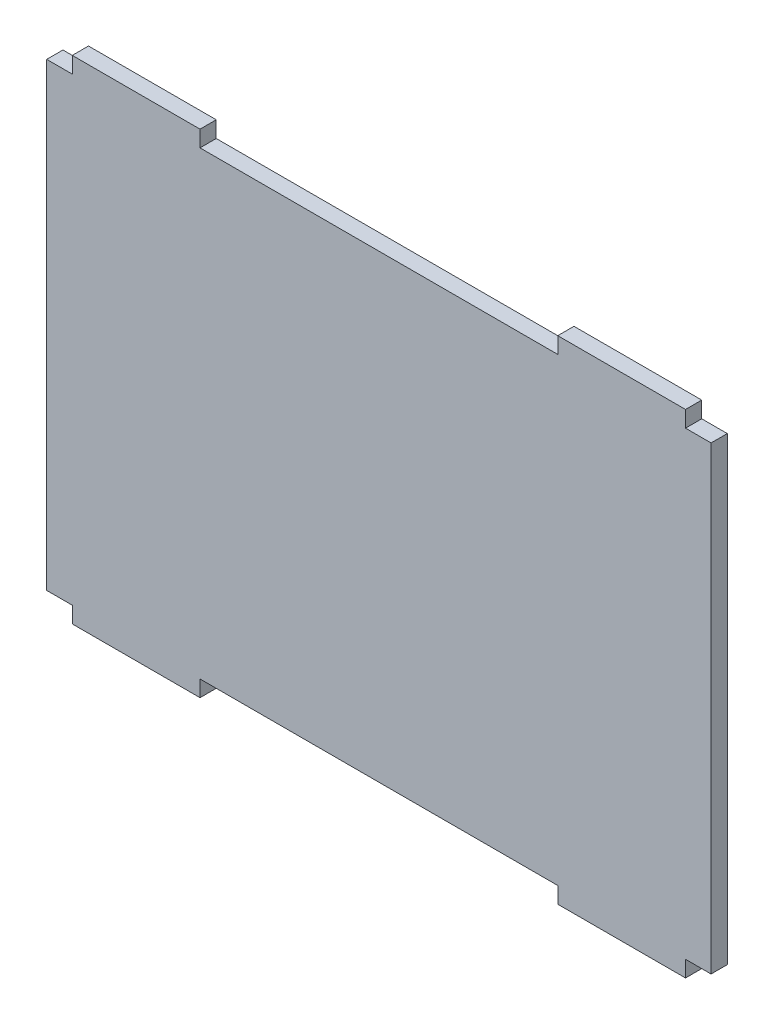
SolidWorks part; units mm, degrees
ref_plane "Front Plane" through (0, 0, 0) normal (0, 0, 1) x (1, 0, 0)
ref_plane "Top Plane" through (0, 0, 0) normal (0, 1, 0) x (1, 0, 0)
ref_plane "Right Plane" through (0, 0, 0) normal (1, 0, 0) x (0, 0, -1)
sketch "Sketch1" plane through (0, 0, 0) normal (0, 0, 1) x (1, 0, 0)
  line L0 (5, 0) -> (5, -3.175)
  line L1 (0, 0) -> (5, 0)
  line L2 (0, 0) -> (0, 90)
  line L3 (0, 90) -> (5, 90)
  line L4 (130, 0) -> (130, 90)
  line L5 (5, -3.175) -> (30, -3.175)
  line L6 (30, -3.175) -> (30, 0)
  line L7 (125, 0) -> (125, -3.175)
  line L8 (125, -3.175) -> (100, -3.175)
  line L9 (100, -3.175) -> (100, 0)
  line L10 (125, 90) -> (125, 93.175)
  line L11 (125, 93.175) -> (100, 93.175)
  line L12 (100, 93.175) -> (100, 90)
  line L13 (30, 90) -> (30, 93.175)
  line L14 (30, 93.175) -> (5, 93.175)
  line L15 (5, 93.175) -> (5, 90)
  line L16 (30, 90) -> (100, 90)
  line L17 (125, 90) -> (130, 90)
  line L18 (30, 0) -> (100, 0)
  line L19 (125, 0) -> (130, 0)
  dimension "D3" = 25
  dimension "D1" = 90
  dimension "D2" = 130
  dimension "D4" = 3.175
  dimension "D5" = 5
  dimension "D6" = 5
  dimension "D7" = 5
  dimension "D8" = 5
extrude "Boss-Extrude1" add sketch "Sketch1" along normal blind 3.175
